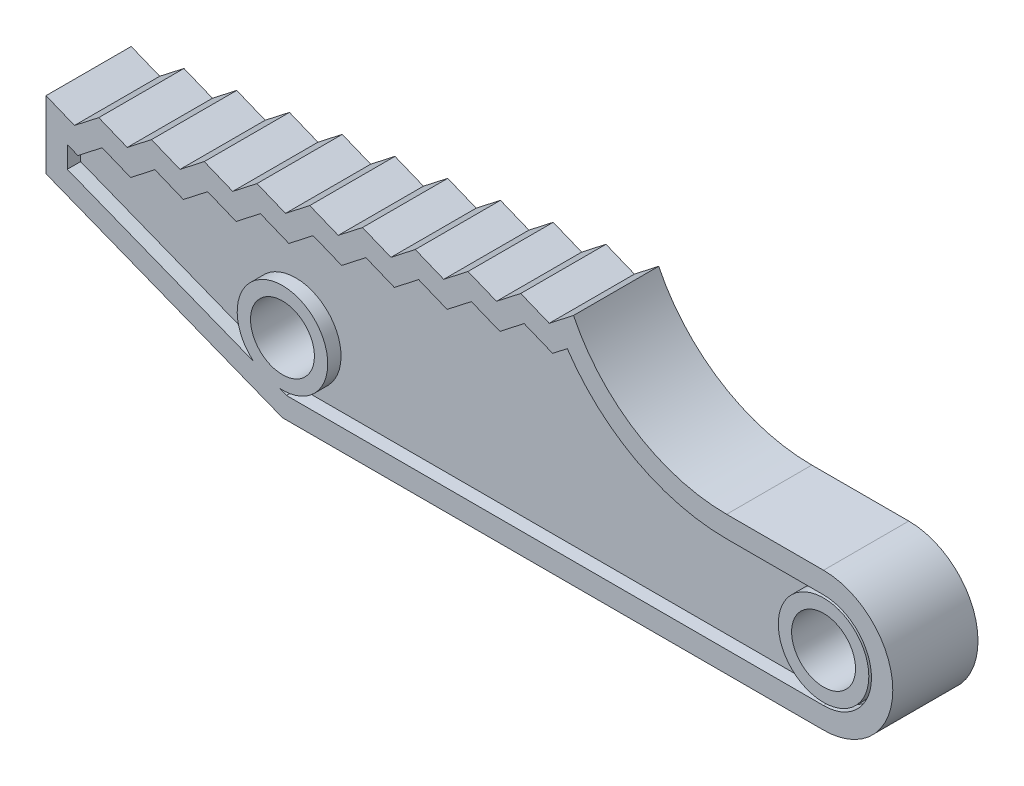
SolidWorks part; units mm, degrees
ref_plane "Front Plane" through (0, 0, 0) normal (0, 0, 1) x (1, 0, 0)
ref_plane "Top Plane" through (0, 0, 0) normal (0, 1, 0) x (1, 0, 0)
ref_plane "Right Plane" through (0, 0, 0) normal (1, 0, 0) x (0, 0, -1)
sketch "Sketch1" plane through (0, 0, 0) normal (0, 0, 1) x (1, 0, 0)
  line L2 (0, -6.35) -> (0, 0)
  line L5 (73, -15.0877) -> (73, -2.0877) construction
  line L6 (73, -2.0877) -> (63.8995, -2.0877)
  line L9 (22.2, -15.0877) -> (73, -15.0877)
  line L11 (49.5231, 6.8895) -> (0, 0)
  line L12 (0, -6.35) -> (22.2, -15.0877)
  arc A1 (73, -15.0877) -> (73, -2.0877) centre (73, -8.5877) ccw
  arc A2 (49.5231, 6.8895) -> (63.8995, -2.0877) centre (63.8995, 13.9123) ccw
  circle A3 centre (73, -8.5877) radius 3
  circle A4 centre (22.2, -8.5877) radius 3
  point P3 (31.4472, 4.3748)
  point P4 (59.88, 8.3303)
  point P9 (59.8796, 7.6767)
  point P10 (59.8796, 7.6767)
  point P15 (75.07, -2.0877)
  dimension "D9" = 6.35
  dimension "D5" = 50
  dimension "D6" = 6
  dimension "D7" = 6
  dimension "D11" = 23.8577
  dimension "D3" = 16
  dimension "D2" = 73
  dimension "D4" = 7.92
  dimension "D8" = 50.8
  dimension "D10" = 13
extrude "Boss-Extrude1" add sketch "Sketch1" along normal mid plane 8
sketch "Sketch5" plane through (0, 0, 4) normal (0, 0, 1) x (1, 0, 0)
  line L0 (0, 0) -> (2.675, -1.0851)
  line L1 (2.675, -1.0851) -> (4.9523, 0.689)
  line L2 (49.5231, 6.8895) -> (0, 0) construction
  line L3 (4.9523, 0.689) -> (0, 0)
  line L7 (4.9523, 0.689) -> (9.9046, 1.3779)
  line L9 (9.9046, 1.3779) -> (7.6273, -0.3962)
  line L10 (7.6273, -0.3962) -> (4.9523, 0.689)
  line L11 (9.9046, 1.3779) -> (14.8569, 2.0669)
  line L12 (14.8569, 2.0669) -> (12.5797, 0.2928)
  line L15 (12.5797, 0.2928) -> (9.9046, 1.3779)
  line L16 (14.8569, 2.0669) -> (19.8092, 2.7558)
  line L19 (19.8092, 2.7558) -> (17.532, 0.9817)
  line L20 (17.532, 0.9817) -> (14.8569, 2.0669)
  line L25 (29.7138, 4.1337) -> (27.4366, 2.3596)
  line L26 (19.8092, 2.7558) -> (24.7615, 3.4448)
  line L27 (49.5231, 6.8895) -> (0, 0) construction
  line L29 (19.8092, 2.7558) -> (22.4843, 1.6707)
  line L30 (22.4843, 1.6707) -> (24.7615, 3.4448)
  line L31 (24.7615, 3.4448) -> (29.7138, 4.1337)
  line L32 (27.4366, 2.3596) -> (24.7615, 3.4448)
  line L33 (29.7138, 4.1337) -> (34.6661, 4.8227)
  line L34 (34.6661, 4.8227) -> (32.3889, 3.0486)
  line L35 (32.3889, 3.0486) -> (29.7138, 4.1337)
  line L36 (34.6661, 4.8227) -> (39.6185, 5.5116)
  line L37 (39.6185, 5.5116) -> (37.3412, 3.7375)
  line L38 (37.3412, 3.7375) -> (34.6661, 4.8227)
  line L39 (39.6185, 5.5116) -> (44.5708, 6.2006)
  line L40 (44.5708, 6.2006) -> (42.2935, 4.4265)
  line L41 (42.2935, 4.4265) -> (39.6185, 5.5116)
  line L42 (44.5708, 6.2006) -> (49.5231, 6.8895)
  line L43 (49.5231, 6.8895) -> (47.2458, 5.1154)
  line L44 (47.2458, 5.1154) -> (44.5708, 6.2006)
  dimension "D1" = 30
  dimension "D2" = 30
  dimension "D3" = 5
  dimension "D4" = 5
  dimension "D5" = 30
  dimension "D6" = 30
  dimension "D7" = 5
  dimension "D8" = 30
  dimension "D9" = 30
  dimension "D10" = 5
  dimension "D11" = 30
  dimension "D12" = 30
  dimension "D13" = 5
  dimension "D14" = 30
  dimension "D15" = 30
  dimension "D16" = 5
  dimension "D17" = 30
  dimension "D18" = 30
  dimension "D19" = 5
  dimension "D20" = 30
  dimension "D21" = 30
  dimension "D22" = 5
  dimension "D23" = 30
  dimension "D24" = 30
  dimension "D25" = 5
  dimension "D26" = 30
  dimension "D27" = 30
  dimension "D28" = 30
  dimension "D29" = 30
extrude "Cut-Extrude3" cut sketch "Sketch5" against normal through all
sketch "Sketch4" plane through (0, 0, 4) normal (0, 0, 1) x (1, 0, 0)
  line L5 (20.1274, 0.4684) -> (17.8502, -1.3057)
  line L7 (22.5794, -13.0877) -> (73, -13.0877)
  line L8 (22.5794, -13.0877) -> (73, -13.0877)
  line L13 (2, -4.9878) -> (22.5794, -13.0877)
  line L14 (2, -4.9878) -> (22.5794, -13.0877)
  line L16 (73, -4.0877) -> (63.8995, -4.0877)
  line L20 (2, -2.9696) -> (2, -4.9878)
  line L23 (73, -4.0877) -> (63.8995, -4.0877)
  line L27 (2, -2.9696) -> (2, -4.9878)
  line L49 (20.1274, 0.4684) -> (17.8502, -1.3057)
  line L51 (17.8502, -1.3057) -> (15.1751, -0.2205)
  line L53 (17.8502, -1.3057) -> (15.1751, -0.2205)
  line L54 (15.1751, -0.2205) -> (12.8979, -1.9946)
  line L55 (15.1751, -0.2205) -> (12.8979, -1.9946)
  line L56 (12.8979, -1.9946) -> (10.2228, -0.9095)
  line L57 (12.8979, -1.9946) -> (10.2228, -0.9095)
  line L58 (10.2228, -0.9095) -> (7.9456, -2.6836)
  line L59 (10.2228, -0.9095) -> (7.9456, -2.6836)
  line L60 (7.9456, -2.6836) -> (5.2705, -1.5984)
  line L61 (7.9456, -2.6836) -> (5.2705, -1.5984)
  line L62 (5.2705, -1.5984) -> (2.9932, -3.3725)
  line L63 (5.2705, -1.5984) -> (2.9932, -3.3725)
  line L64 (2.9932, -3.3725) -> (2, -2.9696)
  line L65 (2.9932, -3.3725) -> (2, -2.9696)
  line L66 (34.9844, 2.5353) -> (32.7071, 0.7612)
  line L67 (34.9844, 2.5353) -> (32.7071, 0.7612)
  line L68 (32.7071, 0.7612) -> (30.0321, 1.8463)
  line L69 (32.7071, 0.7612) -> (30.0321, 1.8463)
  line L70 (30.0321, 1.8463) -> (27.7548, 0.0723)
  line L71 (30.0321, 1.8463) -> (27.7548, 0.0723)
  line L72 (27.7548, 0.0723) -> (25.0797, 1.1574)
  line L73 (27.7548, 0.0723) -> (25.0797, 1.1574)
  line L74 (25.0797, 1.1574) -> (22.8025, -0.6167)
  line L75 (25.0797, 1.1574) -> (22.8025, -0.6167)
  line L76 (22.8025, -0.6167) -> (20.1274, 0.4684)
  line L77 (22.8025, -0.6167) -> (20.1274, 0.4684)
  line L78 (48.9407, 3.9005) -> (47.564, 2.8281)
  line L80 (48.9407, 3.9005) -> (47.564, 2.8281)
  line L82 (47.564, 2.8281) -> (44.889, 3.9132)
  line L84 (42.6117, 2.1391) -> (39.9367, 3.2242)
  line L85 (42.6117, 2.1391) -> (39.9367, 3.2242)
  line L86 (39.9367, 3.2242) -> (37.6594, 1.4502)
  line L87 (39.9367, 3.2242) -> (37.6594, 1.4502)
  line L88 (37.6594, 1.4502) -> (34.9844, 2.5353)
  line L89 (37.6594, 1.4502) -> (34.9844, 2.5353)
  line L90 (47.564, 2.8281) -> (44.889, 3.9132)
  line L91 (44.889, 3.9132) -> (42.6117, 2.1391)
  line L92 (44.889, 3.9132) -> (42.6117, 2.1391)
  arc A6 (73, -13.0877) -> (73, -4.0877) centre (73, -8.5877) ccw
  arc A7 (48.9407, 3.9005) -> (63.8995, -4.0877) centre (63.8995, 13.9123) ccw
  arc A9 (73, -13.0877) -> (73, -4.0877) centre (73, -8.5877) ccw
  arc A10 (48.9407, 3.9005) -> (63.8995, -4.0877) centre (63.8995, 13.9123) ccw
  dimension "D1" = 2
extrude "Cut-Extrude2" cut sketch "Sketch4" against normal blind 1.25
sketch "Sketch6" plane through (0, 0, 2.75) normal (0, 0, 1) x (1, 0, 0)
  circle A0 centre (22.2, -8.5877) radius 4.25
  circle A1 centre (22.2, -8.5877) radius 3 construction
  circle A2 centre (73, -8.5877) radius 4.25
  circle A3 centre (73, -8.5877) radius 3 construction
  circle A4 centre (22.2, -8.5877) radius 3
  circle A5 centre (73, -8.5877) radius 3
  dimension "D1" = 1.25
  dimension "D2" = 1.25
  dimension "D3" = 6
  dimension "D4" = 6
extrude "Boss-Extrude2" add sketch "Sketch6" along normal blind 1.25
sketch "Sketch7" plane through (0, 0, -4) normal (0, 0, -1) x (-1, 0, 0)
  line L16 (-17.532, 0.9817) -> (-19.8092, 2.7558)
  line L17 (-14.8569, 2.0669) -> (-17.532, 0.9817)
  line L18 (-12.5797, 0.2928) -> (-14.8569, 2.0669)
  line L19 (-9.9046, 1.3779) -> (-12.5797, 0.2928)
  line L20 (-7.6273, -0.3962) -> (-9.9046, 1.3779)
  line L21 (-4.9523, 0.689) -> (-7.6273, -0.3962)
  line L22 (-2.675, -1.0851) -> (-4.9523, 0.689)
  line L23 (0, 0) -> (-2.675, -1.0851)
  line L24 (0, -6.35) -> (0, 0)
  line L25 (-22.2, -15.0877) -> (0, -6.35)
  line L26 (-73, -15.0877) -> (-22.2, -15.0877)
  line L27 (-63.8995, -2.0877) -> (-73, -2.0877)
  line L28 (-32.3889, 3.0486) -> (-34.6661, 4.8227)
  line L29 (-32.3889, 3.0486) -> (-34.6661, 4.8227)
  line L30 (-29.7138, 4.1337) -> (-32.3889, 3.0486)
  line L31 (-29.7138, 4.1337) -> (-32.3889, 3.0486)
  line L32 (-17.532, 0.9817) -> (-19.8092, 2.7558)
  line L33 (-14.8569, 2.0669) -> (-17.532, 0.9817)
  line L34 (-12.5797, 0.2928) -> (-14.8569, 2.0669)
  line L35 (-9.9046, 1.3779) -> (-12.5797, 0.2928)
  line L36 (-7.6273, -0.3962) -> (-9.9046, 1.3779)
  line L37 (-4.9523, 0.689) -> (-7.6273, -0.3962)
  line L38 (-2.675, -1.0851) -> (-4.9523, 0.689)
  line L39 (0, 0) -> (-2.675, -1.0851)
  line L40 (0, -6.35) -> (0, 0)
  line L41 (-22.2, -15.0877) -> (0, -6.35)
  line L42 (-73, -15.0877) -> (-22.2, -15.0877)
  line L43 (-63.8995, -2.0877) -> (-73, -2.0877)
  line L48 (-20.1274, 0.4684) -> (-22.8025, -0.6167)
  line L49 (-17.8502, -1.3057) -> (-20.1274, 0.4684)
  line L50 (-15.1751, -0.2205) -> (-17.8502, -1.3057)
  line L51 (-12.8979, -1.9946) -> (-15.1751, -0.2205)
  line L52 (-10.2228, -0.9095) -> (-12.8979, -1.9946)
  line L53 (-7.9456, -2.6836) -> (-10.2228, -0.9095)
  line L54 (-5.2705, -1.5984) -> (-7.9456, -2.6836)
  line L55 (-2.9932, -3.3725) -> (-5.2705, -1.5984)
  line L56 (-2, -2.9696) -> (-2.9932, -3.3725)
  line L57 (-2, -4.9878) -> (-2, -2.9696)
  line L58 (-19.5137, -11.8811) -> (-2, -4.9878)
  line L59 (-73, -13.0877) -> (-22.5794, -13.0877)
  line L60 (-63.8995, -4.0877) -> (-73, -4.0877)
  line L61 (-20.1274, 0.4684) -> (-22.8025, -0.6167)
  line L65 (-17.8502, -1.3057) -> (-20.1274, 0.4684)
  line L66 (-15.1751, -0.2205) -> (-17.8502, -1.3057)
  line L67 (-12.8979, -1.9946) -> (-15.1751, -0.2205)
  line L68 (-10.2228, -0.9095) -> (-12.8979, -1.9946)
  line L69 (-7.9456, -2.6836) -> (-10.2228, -0.9095)
  line L70 (-5.2705, -1.5984) -> (-7.9456, -2.6836)
  line L71 (-2.9932, -3.3725) -> (-5.2705, -1.5984)
  line L72 (-2, -2.9696) -> (-2.9932, -3.3725)
  line L73 (-2, -4.9878) -> (-2, -2.9696)
  line L74 (-19.5137, -11.8811) -> (-2, -4.9878)
  line L75 (-73, -13.0877) -> (-22.5794, -13.0877)
  line L76 (-63.8995, -4.0877) -> (-73, -4.0877)
  line L87 (-47.2458, 5.1154) -> (-49.5231, 6.8895)
  line L88 (-27.4366, 2.3596) -> (-29.7138, 4.1337)
  line L89 (-27.4366, 2.3596) -> (-29.7138, 4.1337)
  line L90 (-24.7615, 3.4448) -> (-27.4366, 2.3596)
  line L91 (-24.7615, 3.4448) -> (-27.4366, 2.3596)
  line L92 (-22.4843, 1.6707) -> (-24.7615, 3.4448)
  line L93 (-22.4843, 1.6707) -> (-24.7615, 3.4448)
  line L94 (-19.8092, 2.7558) -> (-22.4843, 1.6707)
  line L95 (-19.8092, 2.7558) -> (-22.4843, 1.6707)
  line L96 (-47.2458, 5.1154) -> (-49.5231, 6.8895)
  line L98 (-44.5708, 6.2006) -> (-47.2458, 5.1154)
  line L100 (-44.5708, 6.2006) -> (-47.2458, 5.1154)
  line L102 (-39.6185, 5.5116) -> (-42.2935, 4.4265)
  line L103 (-39.6185, 5.5116) -> (-42.2935, 4.4265)
  line L104 (-37.3412, 3.7375) -> (-39.6185, 5.5116)
  line L105 (-37.3412, 3.7375) -> (-39.6185, 5.5116)
  line L106 (-34.6661, 4.8227) -> (-37.3412, 3.7375)
  line L107 (-34.6661, 4.8227) -> (-37.3412, 3.7375)
  line L108 (-42.2935, 4.4265) -> (-44.5708, 6.2006)
  line L110 (-42.2935, 4.4265) -> (-44.5708, 6.2006)
  line L112 (-39.9367, 3.2242) -> (-42.6117, 2.1391)
  line L113 (-39.9367, 3.2242) -> (-42.6117, 2.1391)
  line L114 (-37.6594, 1.4502) -> (-39.9367, 3.2242)
  line L115 (-37.6594, 1.4502) -> (-39.9367, 3.2242)
  line L116 (-34.9844, 2.5353) -> (-37.6594, 1.4502)
  line L117 (-34.9844, 2.5353) -> (-37.6594, 1.4502)
  line L118 (-32.7071, 0.7612) -> (-34.9844, 2.5353)
  line L119 (-32.7071, 0.7612) -> (-34.9844, 2.5353)
  line L120 (-30.0321, 1.8463) -> (-32.7071, 0.7612)
  line L121 (-30.0321, 1.8463) -> (-32.7071, 0.7612)
  line L122 (-27.7548, 0.0723) -> (-30.0321, 1.8463)
  line L123 (-27.7548, 0.0723) -> (-30.0321, 1.8463)
  line L124 (-25.0797, 1.1574) -> (-27.7548, 0.0723)
  line L125 (-25.0797, 1.1574) -> (-27.7548, 0.0723)
  line L126 (-22.8025, -0.6167) -> (-25.0797, 1.1574)
  line L127 (-22.8025, -0.6167) -> (-25.0797, 1.1574)
  line L128 (-47.564, 2.8281) -> (-48.9407, 3.9005)
  line L129 (-47.564, 2.8281) -> (-48.9407, 3.9005)
  line L130 (-44.889, 3.9132) -> (-47.564, 2.8281)
  line L131 (-44.889, 3.9132) -> (-47.564, 2.8281)
  line L132 (-42.6117, 2.1391) -> (-44.889, 3.9132)
  line L133 (-42.6117, 2.1391) -> (-44.889, 3.9132)
  line L135 (-22.5794, -13.0877) -> (-21.9209, -12.8286)
  line L136 (-22.5794, -13.0877) -> (-21.9209, -12.8286)
  circle A0 centre (-73, -8.5877) radius 4.25
  circle A1 centre (-73, -8.5877) radius 3 construction
  circle A2 centre (-22.2, -8.5877) radius 4.25
  arc A3 (-73, -2.0877) -> (-73, -15.0877) centre (-73, -8.5877) ccw
  arc A4 (-63.8995, -2.0877) -> (-49.5231, 6.8895) centre (-63.8995, 13.9123) ccw
  arc A6 (-73, -2.0877) -> (-73, -15.0877) centre (-73, -8.5877) ccw
  arc A7 (-63.8995, -2.0877) -> (-49.5231, 6.8895) centre (-63.8995, 13.9123) ccw
  arc A9 (-73, -4.0877) -> (-73, -13.0877) centre (-73, -8.5877) ccw
  arc A10 (-63.8995, -4.0877) -> (-48.9407, 3.9005) centre (-63.8995, 13.9123) ccw
  arc A12 (-73, -4.0877) -> (-73, -13.0877) centre (-73, -8.5877) ccw
  arc A13 (-63.8995, -4.0877) -> (-48.9407, 3.9005) centre (-63.8995, 13.9123) ccw
  circle A15 centre (-22.2, -8.5877) radius 3 construction
  arc A17 (-19.5137, -11.8811) -> (-21.9209, -12.8286) centre (-22.2, -8.5877) ccw
  arc A18 (-19.5137, -11.8811) -> (-21.9209, -12.8286) centre (-22.2, -8.5877) ccw
  dimension "D3" = 1.25
  dimension "D4" = 1.25
  dimension "D1" = 0
  dimension "D2" = 0
extrude "Cut-Extrude4" cut sketch "Sketch7" against normal blind 1.2
